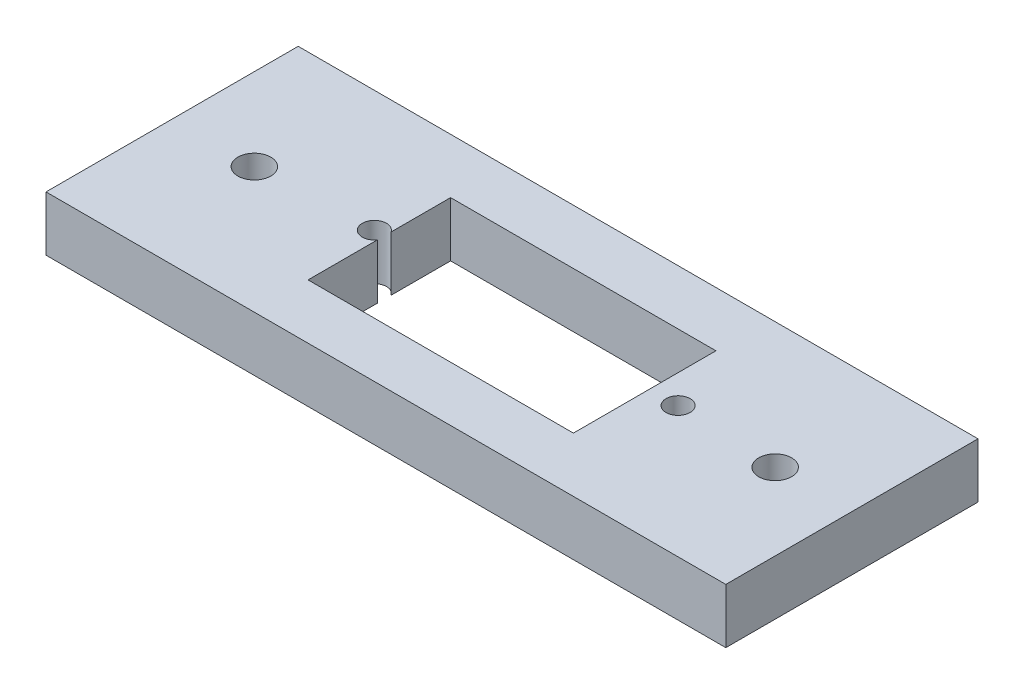
SolidWorks part; units mm, degrees
ref_plane "Front Plane" through (0, 0, 0) normal (0, 0, 1) x (1, 0, 0)
ref_plane "Top Plane" through (0, 0, 0) normal (0, 1, 0) x (1, 0, 0)
ref_plane "Right Plane" through (0, 0, 0) normal (1, 0, 0) x (0, 0, -1)
sketch "Sketch4" plane through (0, 0, 0) normal (0, 1, 0) x (1, 0, 0)
  line L1 (0, 0) -> (62, 0)
  line L2 (0, 0) -> (0, 23)
  line L3 (0, 23) -> (62, 23)
  line L4 (62, 0) -> (62, 23)
  line L5 (18.9, 18) -> (43.1, 18)
  line L6 (18.9, 18) -> (18.9, 5)
  line L7 (18.9, 5) -> (43.1, 5)
  line L8 (43.1, 18) -> (43.1, 5)
  line L9 (18.9, 18) -> (43.1, 5) construction
  line L10 (18.9, 5) -> (43.1, 18) construction
  point P5 (31, 11.5)
  point P10 (31, 0)
  point P11 (0, 11.5)
  dimension "D1" = 62
  dimension "D2" = 23
  dimension "D3" = 24.2
  dimension "D4" = 13
extrude "Boss-Extrude2" add sketch "Sketch4" along normal blind 5
ref_plane "Plane1" through (43.1, 5, -18) normal (-1, 0, 0) x (0, 0, 1)
sketch "Sketch7" plane through (0, 5, 0) normal (0, 1, 0) x (1, 0, 0)
  line L0 (62, 11.5) -> (0, 11.5) construction
  line L1 (62, 0) -> (62, 23) construction
  line L2 (0, 23) -> (0, 0) construction
  circle A0 centre (45.7, 11.95) radius 1.1
  circle A1 centre (18, 11.95) radius 1.1
  circle A2 centre (7.5, 11.5) radius 1.5
  circle A3 centre (55, 11.5) radius 1.5
  dimension "D1" = 2.2
  dimension "D2" = 2.2
  dimension "D5" = 3
  dimension "D3" = 7.5
  dimension "D4" = 7
extrude "Cut-Extrude3" cut sketch "Sketch7" against normal blind 10
